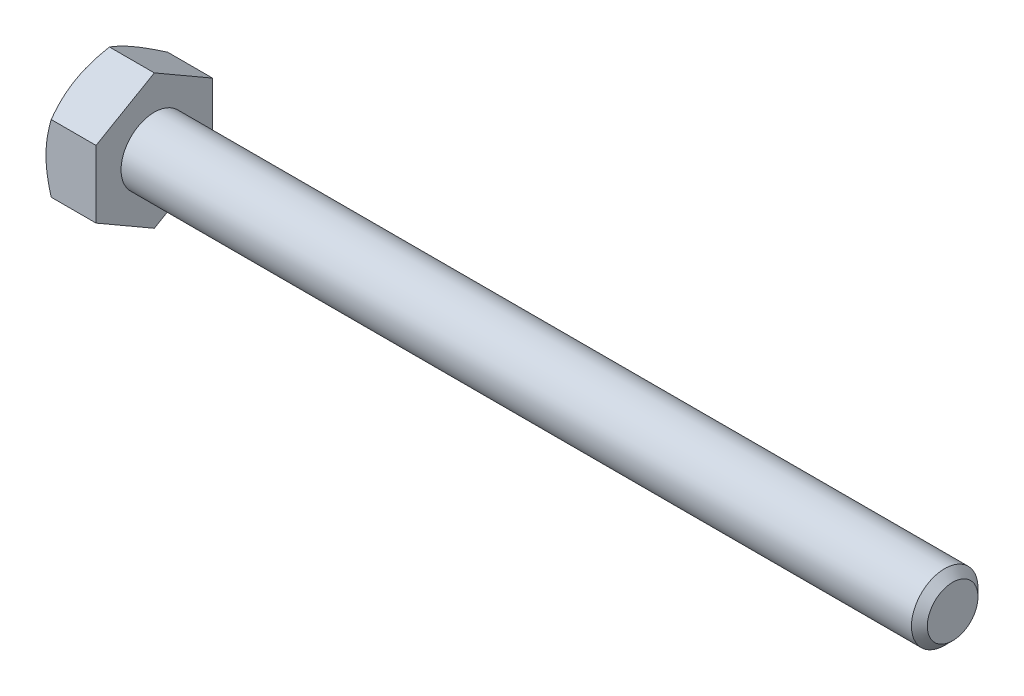
SolidWorks part; units mm, degrees
ref_plane "Plane1" through (0, 0, 0) normal (0, 0, 1) x (1, 0, 0)
ref_plane "Plane2" through (0, 0, 0) normal (0, 1, 0) x (1, 0, 0)
ref_plane "Plane3" through (0, 0, 0) normal (1, 0, 0) x (0, 0, -1)
sketch "Sketch1" plane through (0, 0, 0) normal (1, 0, 0) x (0, 0, -1)
  line L0 (5.5626, 3.2116) -> (5.5626, -3.2116)
  line L1 (-5.5626, 3.2116) -> (-5.5626, -3.2116)
  line L2 (5.5626, -3.2116) -> (0, -6.4231)
  line L3 (0, -6.4231) -> (-5.5626, -3.2116)
  line L4 (5.5626, 3.2116) -> (0, 6.4231)
  line L5 (0, 6.4231) -> (-5.5626, 3.2116)
  dimension "Width_flats" = 11.1252
  dimension "D2" = 120
  dimension "D3" = 5.5626
  dimension "D4" = 5.5626
  dimension "D5" = 5.5626
extrude "BaseHead" add sketch "Sketch1" along normal blind 4.7752
sketch "BodySke" plane through (0, 0, 0) normal (0, 0, 1) x (1, 0, 0)
  line L0 (0, 3.2116) -> (0, -3.2116) construction
  line L1 (0, 0) -> (80.9752, 0)
  line L2 (0, 0) -> (0, 3.175)
  line L3 (0, 3.175) -> (80.2195, 3.175)
  line L4 (80.9752, 0) -> (80.9752, 2.4193)
  line L5 (4.7752, 6.4231) -> (4.7752, 3.2116) construction
  line L6 (80.9752, 2.4193) -> (80.2195, 3.175)
  line L7 (0, 0) -> (96.52, 0) construction
  line L8 (80.9752, -2.4193) -> (80.2195, -3.175) construction
  line L9 (0, -3.175) -> (80.2195, -3.175) construction
  line L10 (6.0452, 15.24) -> (6.0452, -2.54) construction
  line L11 (61.9252, 15.24) -> (61.9252, -2.54) construction
  line L12 (4.7752, 3.2116) -> (4.7752, -3.2116) construction
  dimension "Length" = 76.2
  dimension "Body_ch_ang" = 45
  dimension "Diameter" = 6.35
  dimension "Minor_dia" = 4.8387
  dimension "Advance" = 1.27
  dimension "Thread_nom" = 19.05
revolve "BaseBody" add sketch "BodySke" angle 360 about L7
cosmetic thread "ThreadCosmetic" [suppressed] parameters "Thread_length"=19.05, "Thread_minor"=4.8387
sketch "Sketch3" plane through (0, 0, 0) normal (0, 0, 1) x (1, 0, 0)
  line L0 (0, 5.5626) -> (4.163, 12.7731)
  line L1 (0, 6.4231) -> (0, 3.2116) construction
  line L2 (4.163, 12.7731) -> (4.163, 19.1231)
  line L3 (4.163, 19.1231) -> (-12.7, 19.1231)
  line L4 (-12.7, 19.1231) -> (-12.7, 5.5626)
  line L5 (-12.7, 5.5626) -> (0, 5.5626)
  line L6 (0, 0) -> (99.06, 0) construction
  line L7 (4.7752, 6.4231) -> (0, 6.4231) construction
  dimension "D1" = 5.5626
  dimension "D2" = 6.35
  dimension "D3" = 12.7
  dimension "D4" = 6.35
  dimension "Head_ch_ang" = 30
revolve "HeadChamfer" cut sketch "Sketch3" angle 360 about L6
fillet "HeadFillet" [suppressed] radius 0.762
sketch "ThdSchSke" plane through (0, 0, 0) normal (0, 0, 1) x (1, 0, 0)
  line L0 (61.9252, -2.4193) -> (61.3961, -3.175)
  line L1 (61.9252, -2.4193) -> (62.4543, -3.175)
  line L2 (62.4543, -3.175) -> (62.4543, -3.9687)
  line L3 (-3.175, 0) -> (5.1513, 0) construction
  line L5 (62.4543, -3.9687) -> (61.3961, -3.9687)
  line L6 (61.3961, -3.9687) -> (61.3961, -3.175)
  dimension "Thread_minor" = 4.8387
  dimension "Diameter" = 6.35
  dimension "Start" = 61.9252
  dimension "SideAngle" = 55
  dimension "VeeAngle" = 70
  dimension "Overcut" = 7.9375
revolve "ThreadSchematic" [suppressed] cut sketch "ThdSchSke" angle 360 about L3
pattern_linear "ThdSchPat" [suppressed]
equation "\"D3@Sketch1\" = \"Width_flats@Sketch1\" / 2"
equation "\"D4@Sketch1\" = \"D3@Sketch1\""
equation "\"D5@Sketch1\" = \"D4@Sketch1\""
equation "\"Thread_minor@ThreadCosmetic\" = \"Minor_dia@BodySke\""
equation "\"D1@Sketch3\" = \"Width_flats@Sketch1\" / 2"
equation "\"Thread_length@ThreadCosmetic\" = ((sgn( (\"Length@BodySke\" - \"Advance@BodySke\" ) - \"Thread_nom@BodySke\" )-1)*( (\"Length@BodySke\" - \"Advance@BodySke\" ) - \"Thread_nom@BodySke\" ))/-2+ \"Thread_nom@BodySke\""
equation "\"Thread_minor@ThdSchSke\" = \"Minor_dia@BodySke\""
equation "\"Diameter@ThdSchSke\" = \"Diameter@BodySke\""
equation "\"Overcut@ThdSchSke\" = \"Diameter@BodySke\" * 1.25"
equation "\"Start@ThdSchSke\" = \"Head_ht@BaseHead\" + \"Length@BodySke\" - \"Thread_length@ThreadCosmetic\"  '---Non-countersunk---"
equation "\"Num_threads@ThdSchPat\" = int( \"Thread_length@ThreadCosmetic\" / \"Advance@BodySke\" + 0.999 )  + 1"
equation "\"Advance@ThdSchPat\" = \"Thread_length@ThreadCosmetic\" /  (\"Num_threads@ThdSchPat\" - 1) 'relax it"
equation "\"Num_threads@ThdSchPat\" = \"Num_threads@ThdSchPat\" - sgn( \"Num_threads@ThdSchPat\" - 1) '---chamfered tips only---"
